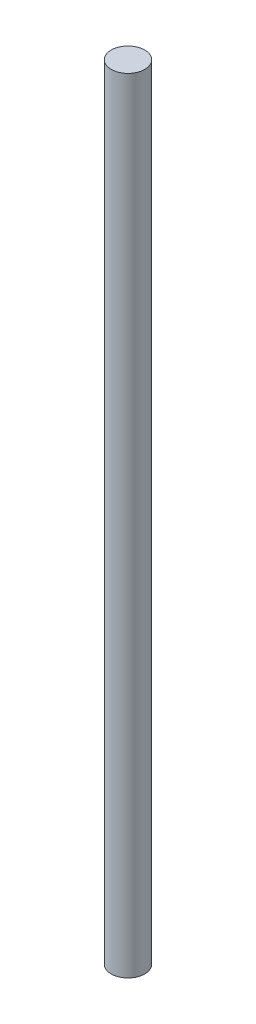
SolidWorks part; units mm, degrees
ref_plane "Front Plane" through (0, 0, 0) normal (0, 0, 1) x (1, 0, 0)
ref_plane "Top Plane" through (0, 0, 0) normal (0, 1, 0) x (1, 0, 0)
ref_plane "Right Plane" through (0, 0, 0) normal (1, 0, 0) x (0, 0, -1)
sketch "Sketch1" plane through (0, 0, 0) normal (0, 1, 0) x (1, 0, 0)
  circle A0 centre (0, 0) radius 3
  dimension "D1" = 6
extrude "Boss-Extrude1" add sketch "Sketch1" along normal blind 140
